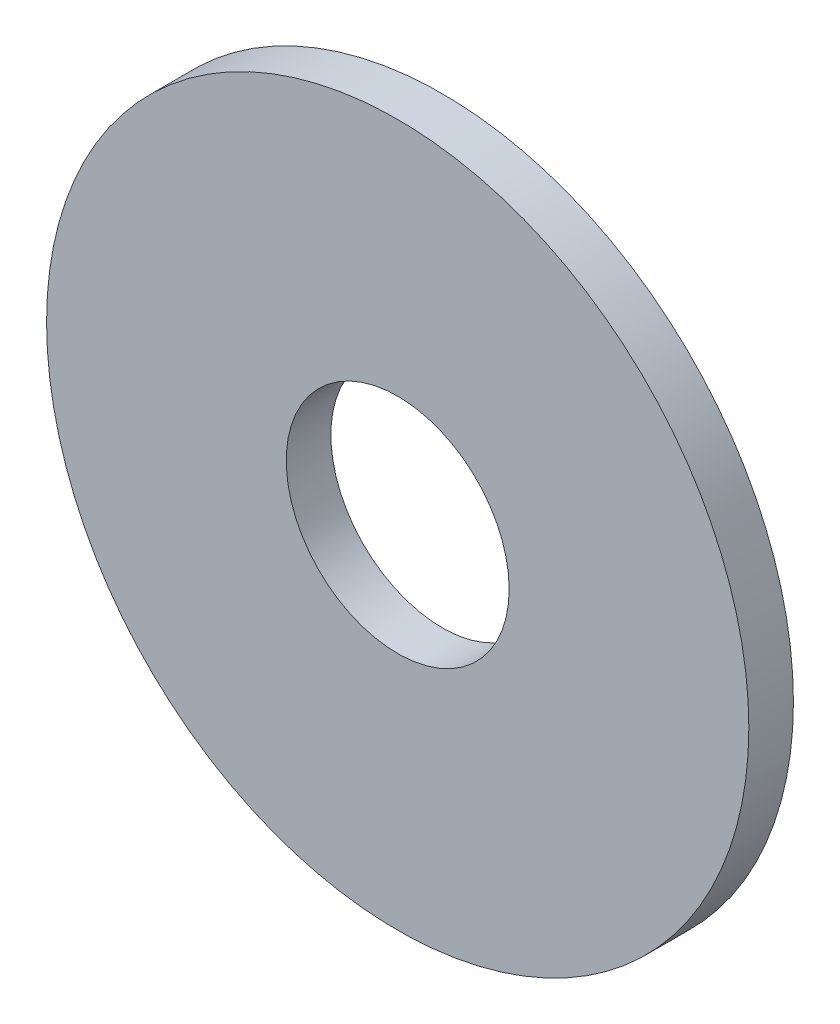
SolidWorks part; units mm, degrees
ref_plane "Front Plane" through (0, 0, 0) normal (0, 0, 1) x (1, 0, 0)
ref_plane "Top Plane" through (0, 0, 0) normal (0, 1, 0) x (1, 0, 0)
ref_plane "Right Plane" through (0, 0, 0) normal (1, 0, 0) x (0, 0, -1)
sketch "Sketch1" plane through (0, 0, 0) normal (0, 0, 1) x (1, 0, 0)
  circle A0 centre (-13.4919, 17.9546) radius 7.875
  circle A1 centre (-13.4919, 17.9546) radius 2.5
extrude "Boss-Extrude1" add sketch "Sketch1" along normal blind 1
